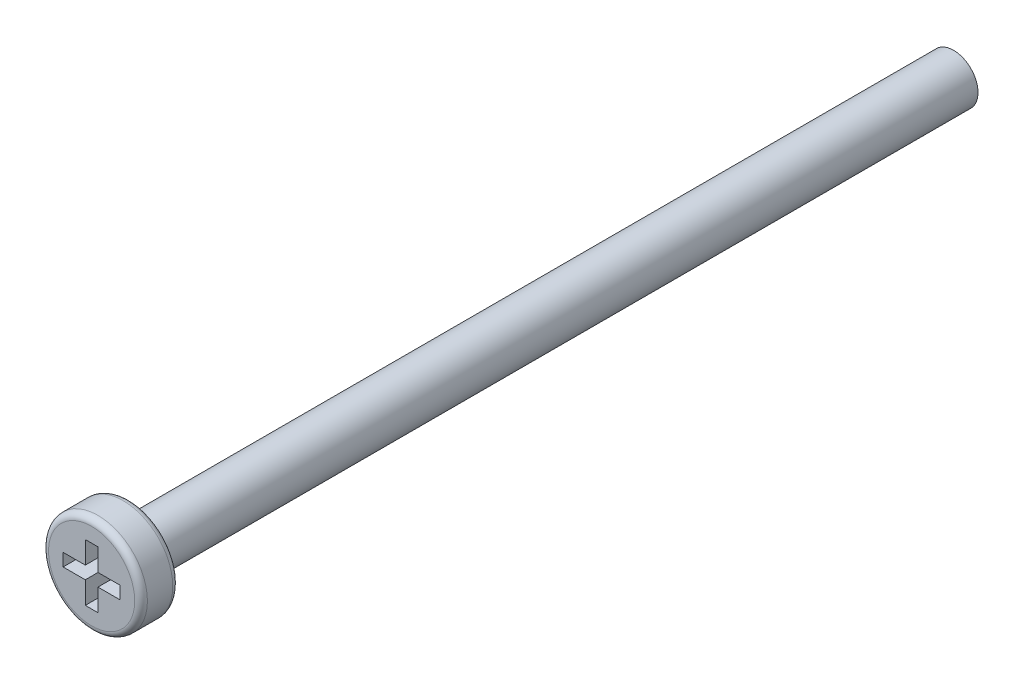
SolidWorks part; units mm, degrees
ref_plane "Plano frontal" through (0, 0, 0) normal (0, 0, 1) x (1, 0, 0)
ref_plane "Plano superior" through (0, 0, 0) normal (0, 1, 0) x (1, 0, 0)
ref_plane "Plano direito" through (0, 0, 0) normal (1, 0, 0) x (0, 0, -1)
sketch "Esboço5" plane through (0, 0, 0) normal (0, 0, 1) x (1, 0, 0)
  circle A0 centre (0, 0) radius 3.9
  dimension "D1" = 7.8
extrude "Ressalto-extrusão2" add sketch "Esboço5" along normal blind 3
sketch "Esboço7" plane through (0, 0, 3) normal (0, 0, 1) x (1, 0, 0)
  line L0 (-0.5, -0.5) -> (-2.25, -0.5)
  line L1 (0.5, 2.25) -> (-0.5, 2.25)
  line L2 (0.5, 2.25) -> (0.5, 0.5)
  line L3 (0.5, -2.25) -> (-0.5, -2.25)
  line L4 (-0.5, 2.25) -> (-0.5, 0.5)
  line L7 (2.25, 0.5) -> (0.5, 0.5)
  line L8 (2.25, 0.5) -> (2.25, -0.5)
  line L9 (2.25, -0.5) -> (0.5, -0.5)
  line L10 (-2.25, 0.5) -> (-2.25, -0.5)
  line L13 (-0.5, -0.5) -> (-0.5, -2.25)
  line L15 (-0.5, 0.5) -> (-2.25, 0.5)
  line L18 (0.5, -0.5) -> (0.5, -2.25)
  point P0 (0, 0)
  point P5 (0, 0)
extrude "Corte-extrusão3" cut sketch "Esboço7" against normal blind 2
fillet "Filete1" radius 0.5 2 edges at (3.9, 0, 0) (3.9, 0, 3)
sketch "Esboço8" plane through (0, 0, 0) normal (0, 0, -1) x (-1, 0, 0)
  circle A0 centre (0, 0) radius 1.925
  dimension "D1" = 3.85
extrude "Ressalto-extrusão3" add sketch "Esboço8" along normal blind 65
